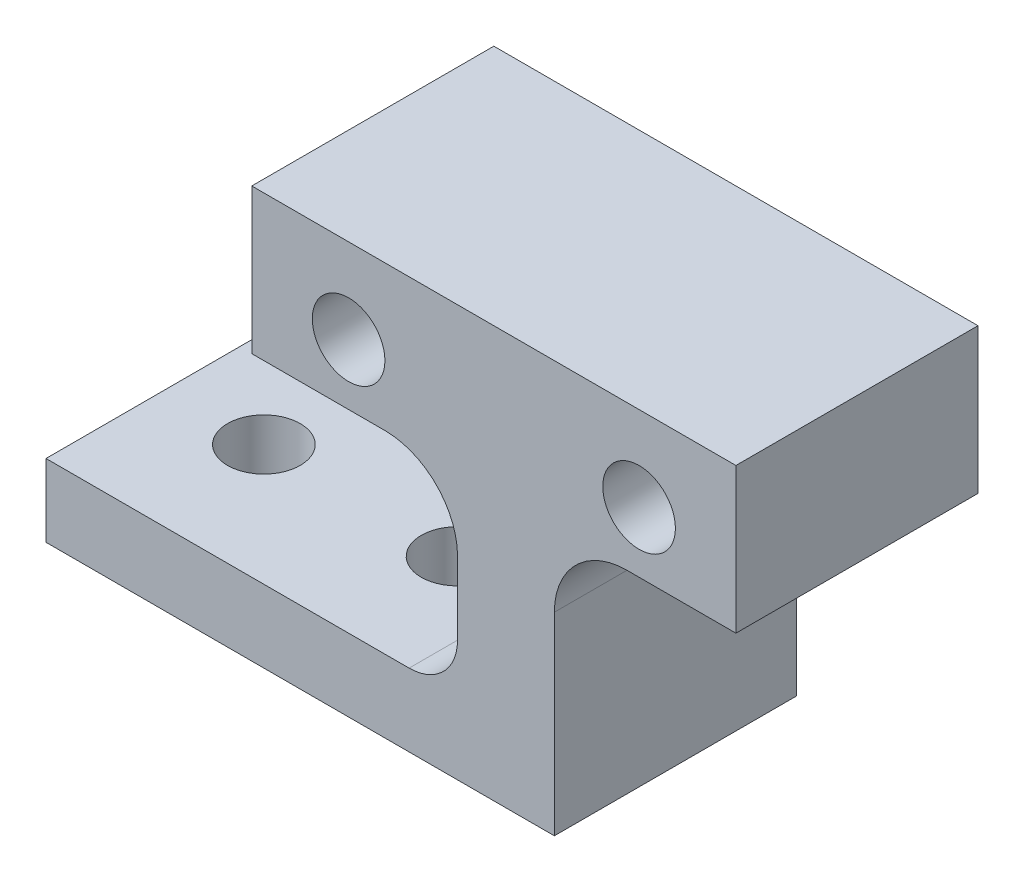
SolidWorks part; units mm, degrees
material "POM 乙缩醛共聚物"
ref_plane "前视基准面" through (0, 0, 0) normal (0, 0, 1) x (1, 0, 0)
ref_plane "上视基准面" through (0, 0, 0) normal (0, 1, 0) x (1, 0, 0)
ref_plane "右视基准面" through (0, 0, 0) normal (1, 0, 0) x (0, 0, -1)
sketch "草图1" plane through (0, 0, 0) normal (0, 1, 0) x (1, 0, 0)
  line L1 (-10, -5) -> (10, -5)
  line L2 (-10, -5) -> (-10, 5)
  line L3 (-10, 5) -> (10, 5)
  line L4 (10, -5) -> (10, 5)
  line L5 (-10, -5) -> (10, 5) construction
  line L6 (-10, 5) -> (10, -5) construction
  point P0 (0, 0)
  dimension "D1" = 10
  dimension "D2" = 20
extrude "凸台-拉伸1" add sketch "草图1" along normal blind 5
sketch "草图2" plane through (0, 0, 5) normal (0, 0, 1) x (1, 0, 0)
  line L0 (-10, 2.5) -> (-6, 2.5) construction
  line L1 (-10, 5) -> (-10, 0) construction
  line L2 (-6, 2.5) -> (6, 2.5) construction
  circle A0 centre (-6, 2.5) radius 1.5
  circle A1 centre (6, 2.5) radius 1.5
  dimension "D3" = 3
  dimension "D4" = 3
  dimension "D1" = 4
  dimension "D2" = 12
extrude "切除-拉伸1" cut sketch "草图2" against normal through all
sketch "草图3" plane through (0, 0, 0) normal (0, -1, 0) x (1, 0, 0)
  line L0 (0, 5) -> (-1.5, 5) construction
  line L1 (-10, 5) -> (10, 5) construction
  line L3 (-1.5, 5) -> (1.5, 5)
  line L4 (-1.5, 5) -> (-1.5, -5)
  line L5 (-1.5, -5) -> (1.5, -5)
  line L6 (1.5, 5) -> (1.5, -5)
  line L7 (10, -5) -> (-10, -5) construction
  dimension "D1" = 1.5
  dimension "D2" = 10
  dimension "D3" = 3
extrude "凸台-拉伸2" add sketch "草图3" along normal blind 8
sketch "草图6" plane through (0, -8, 0) normal (0, -1, 0) x (1, 0, 0)
  line L1 (1.5, -5) -> (-18.5, -5)
  line L2 (1.5, -5) -> (1.5, 5)
  line L3 (1.5, 5) -> (-18.5, 5)
  line L4 (-18.5, -5) -> (-18.5, 5)
  dimension "D1" = 10
  dimension "D2" = 20
extrude "凸台-拉伸4" add sketch "草图6" along normal blind 3
sketch "草图7" plane through (0, -8, 0) normal (0, 1, 0) x (1, 0, 0)
  line L0 (-18.5, 0) -> (-14.5, 0) construction
  line L1 (-18.5, -5) -> (-18.5, 5) construction
  line L2 (-14.5, 0) -> (-6.5, 0) construction
  circle A0 centre (-14.5, 0) radius 1.5
  circle A1 centre (-6.5, 0) radius 1.5
  dimension "D2" = 8
  dimension "D3" = 3
  dimension "D4" = 3
  dimension "D1" = 4
extrude "切除-拉伸3" cut sketch "草图7" against normal through all
fillet "圆角2" radius 3 1 edges at (-1.5, 0, 0)
sketch "草图8" plane through (0, 0, 0) normal (0, 0, 1) x (1, 0, 0)
  line L0 (10, 0) -> (1.5, -11)
fillet "圆角4" radius 2 1 edges at (-1.5, -8, 0)
sketch "草图9" plane through (0, -11, 0) normal (0, -1, 0) x (1, 0, 0)
  line L1 (-18.5, 5) -> (1.5, 5)
  line L2 (-18.5, 5) -> (-18.5, -5)
  line L3 (-18.5, -5) -> (1.5, -5)
  line L4 (1.5, 5) -> (1.5, -5)
  circle A0 centre (-14.5, 0) radius 1.5
  circle A1 centre (-6.5, 0) radius 1.5
  dimension "D1" = 3
sketch "草图11" plane through (1.5, 0, 0) normal (1, 0, 0) x (0, 0, -1)
  line L0 (5, -11) -> (5, 0) construction
  line L1 (-5, -11) -> (5, -11)
  line L2 (-5, -11) -> (-5, 0)
  line L3 (-5, 0) -> (5, 0)
  line L4 (5, -11) -> (5, 0)
extrude "凸台-拉伸7" add sketch "草图11" along normal blind 1
fillet "圆角8" radius 3 1 edges at (2.5, 0, 0)
sketch "草图12" plane through (0, 5, 0) normal (0, 1, 0) x (1, 0, 0)
  line L1 (-10, 5) -> (10, 5)
  line L2 (-10, 5) -> (-10, -5)
  line L3 (-10, -5) -> (10, -5)
  line L4 (10, 5) -> (10, -5)
extrude "凸台-拉伸8" add sketch "草图12" along normal blind 1
